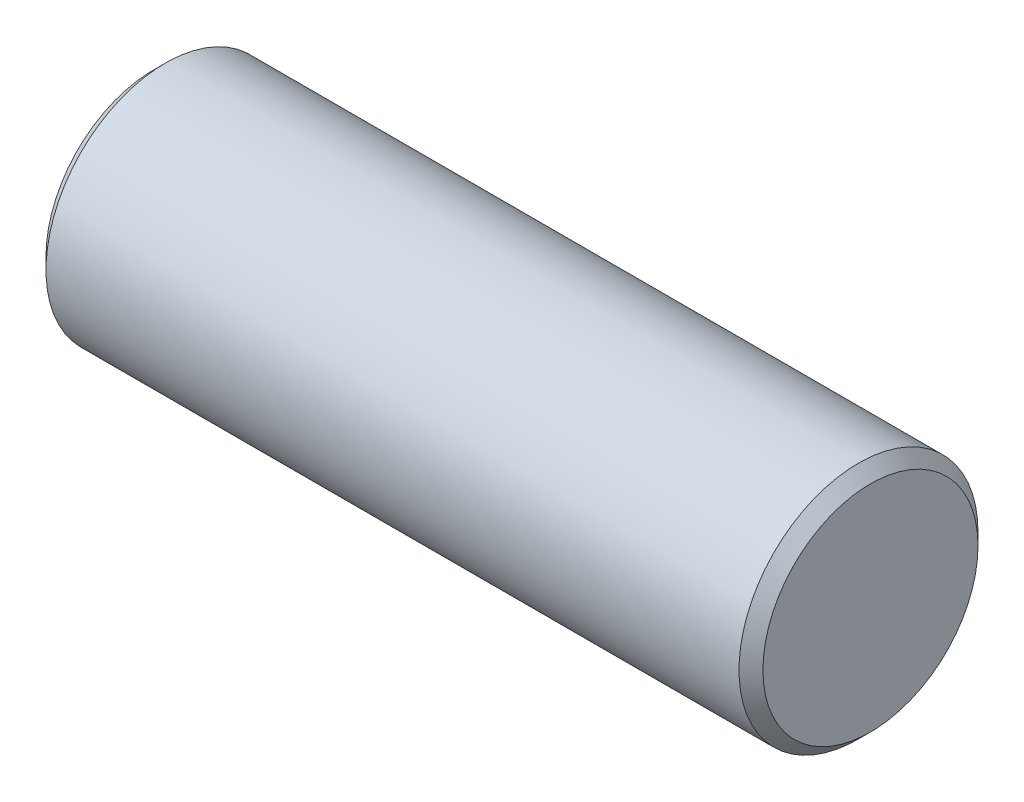
SolidWorks part; units mm, degrees
ref_plane "前视基准面" through (0, 0, 0) normal (0, 0, 1) x (1, 0, 0)
ref_plane "上视基准面" through (0, 0, 0) normal (0, 1, 0) x (1, 0, 0)
ref_plane "右视基准面" through (0, 0, 0) normal (1, 0, 0) x (0, 0, -1)
sketch "草图1" plane through (0, 0, 0) normal (0, 0, 1) x (1, 0, 0)
  line L0 (0, 0) -> (0, 0.5)
  line L1 (0, 0.9) -> (0.1, 1)
  line L2 (6, 0.5) -> (6, 0)
  line L3 (6, 0) -> (0, 0)
  line L4 (0, 0.5) -> (0, 0.9)
  line L5 (0.1, 1) -> (5.9, 1)
  line L6 (6, 0.9) -> (6, 0.5)
  line L7 (5.9, 1) -> (6, 0.9)
  point P4 (6, 1)
  point P10 (0, 1)
revolve "旋转1" add sketch "草图1" angle 360 about L3
